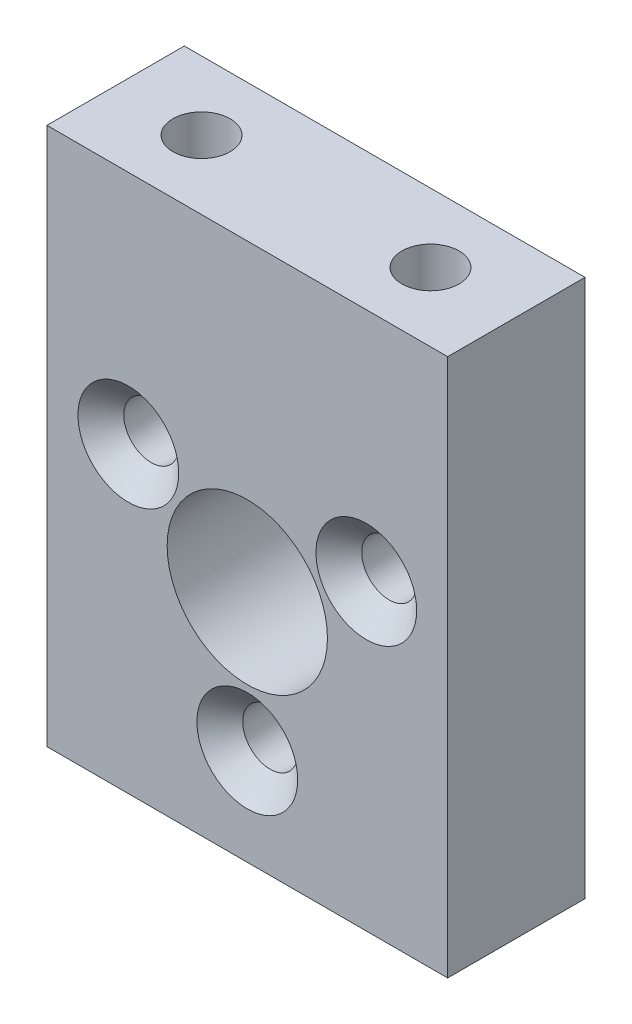
SolidWorks part; units mm, degrees
material "6063-T5"
ref_plane "Front Plane" through (0, 0, 0) normal (0, 0, 1) x (1, 0, 0)
ref_plane "Top Plane" through (0, 0, 0) normal (0, 1, 0) x (1, 0, 0)
ref_plane "Right Plane" through (0, 0, 0) normal (1, 0, 0) x (0, 0, -1)
sketch "Sketch1" plane through (0, 0, 0) normal (0, 0, 1) x (1, 0, 0)
  line L0 (0, -12.925) -> (0, 12.925) construction
  line L5 (-8.75, -11.75) -> (8.75, -11.75)
  line L6 (-8.75, -11.75) -> (-8.75, 11.75)
  line L7 (-8.75, 11.75) -> (8.75, 11.75)
  line L8 (8.75, -11.75) -> (8.75, 11.75)
  line L9 (-8.75, -11.75) -> (8.75, 11.75) construction
  line L10 (-8.75, 11.75) -> (8.75, -11.75) construction
  circle A0 centre (0, -1.53) radius 3.5
  point P0 (0, 0)
  dimension "D4" = 7
  dimension "D1" = 23.5
  dimension "D2" = 17.5
  dimension "D3" = 13.28
extrude "Boss-Extrude1" add sketch "Sketch1" along normal mid plane 6
hole_wizard "CSK for M2 Countersunk Flat Head Screw1" positions "Sketch2" profile "Sketch3" countersink size "M2" standard "DIN" end condition through all
sketch "Sketch2" plane through (0, 0, 3) normal (0, 0, 1) x (1, 0, 0)
  line L0 (0, -3.3) -> (0, 3.3) construction
  circle A0 centre (0, -1.53) radius 6
  point P4 (0, -7.53)
  point P26 (-5.1962, 1.47)
  point P27 (5.1962, 1.47)
  dimension "D1" = 12
  dimension "D2" = 3
sketch "Sketch3" plane through (0, -7.53, 3) normal (1, 0, 0) x (0, -1, 0)
  line L0 (0, 0) -> (0, 6)
  line L1 (0, 6) -> (1.2, 6)
  line L2 (1.2, 6) -> (1.2, 1)
  line L3 (1.2, 1) -> (2.2, 0)
  line L5 (2.2, 0) -> (0, 0)
  line L6 (-1.2, 1) -> (-2.2, 0) construction
  line L11 (0, -6.35) -> (0, 107.95) construction
  dimension "Thru Hole Dia." = 2.4
  dimension "Thru Hole Depth" = 6
  dimension "Near C'Sink Dia." = 4.4
  dimension "Near C'Sink Angle" = 90
hole_wizard "Tap Drill for M3 Tap1" positions "Sketch4" profile "Sketch5" hole size "M3" standard "DIN"
sketch "Sketch4" plane through (0, 11.75, 0) normal (0, 1, 0) x (1, 0, 0)
  line L0 (0, -3.3) -> (0, 3.3) construction
  line L1 (-9.625, 0) -> (9.625, 0) construction
  point P0 (-5, 0)
  point P2 (5, 0)
  dimension "D1" = 5
  dimension "D2" = 10
sketch "Sketch5" plane through (-5, 11.75, 0) normal (1, 0, 0) x (0, 0, 1)
  line L0 (0, 0) -> (0, 6.7511)
  line L1 (0, 6.7511) -> (1.25, 6)
  line L2 (1.25, 6) -> (1.25, 0)
  line L5 (1.25, 0) -> (0, 0)
  line L10 (0, 6.7511) -> (-1.25, 6) construction
  line L11 (0, -6.35) -> (0, 107.95) construction
  dimension "Hole Dia." = 2.5
  dimension "Hole Depth" = 6
  dimension "Drill Angle" = 118
cosmetic thread "Cosmetic Thread1" parameters "D2"=3
cosmetic thread "Cosmetic Thread2" parameters "D2"=3
equation "\"D2@Sketch4\"=\"D1@Sketch4\"*2"
